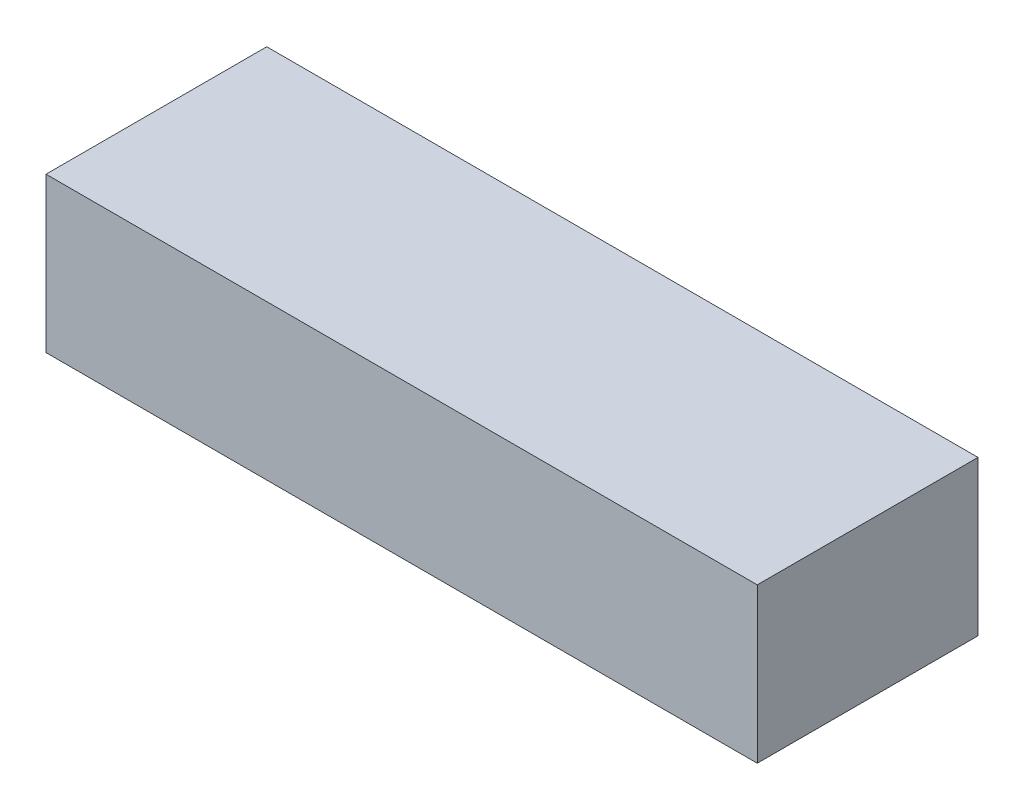
SolidWorks part; units mm, degrees
ref_plane "Front Plane" through (0, 0, 0) normal (0, 0, 1) x (1, 0, 0)
ref_plane "Top Plane" through (0, 0, 0) normal (0, 1, 0) x (1, 0, 0)
ref_plane "Right Plane" through (0, 0, 0) normal (1, 0, 0) x (0, 0, -1)
sketch "Sketch1" plane through (0, 0, 0) normal (0, 1, 0) x (1, 0, 0)
  line L1 (-72.5, -22.5) -> (72.5, -22.5)
  line L2 (-72.5, -22.5) -> (-72.5, 22.5)
  line L3 (-72.5, 22.5) -> (72.5, 22.5)
  line L4 (72.5, -22.5) -> (72.5, 22.5)
  line L5 (-72.5, -22.5) -> (72.5, 22.5) construction
  line L6 (-72.5, 22.5) -> (72.5, -22.5) construction
  point P0 (0, 0)
extrude "Boss-Extrude1" add sketch "Sketch1" along normal blind 31.5
